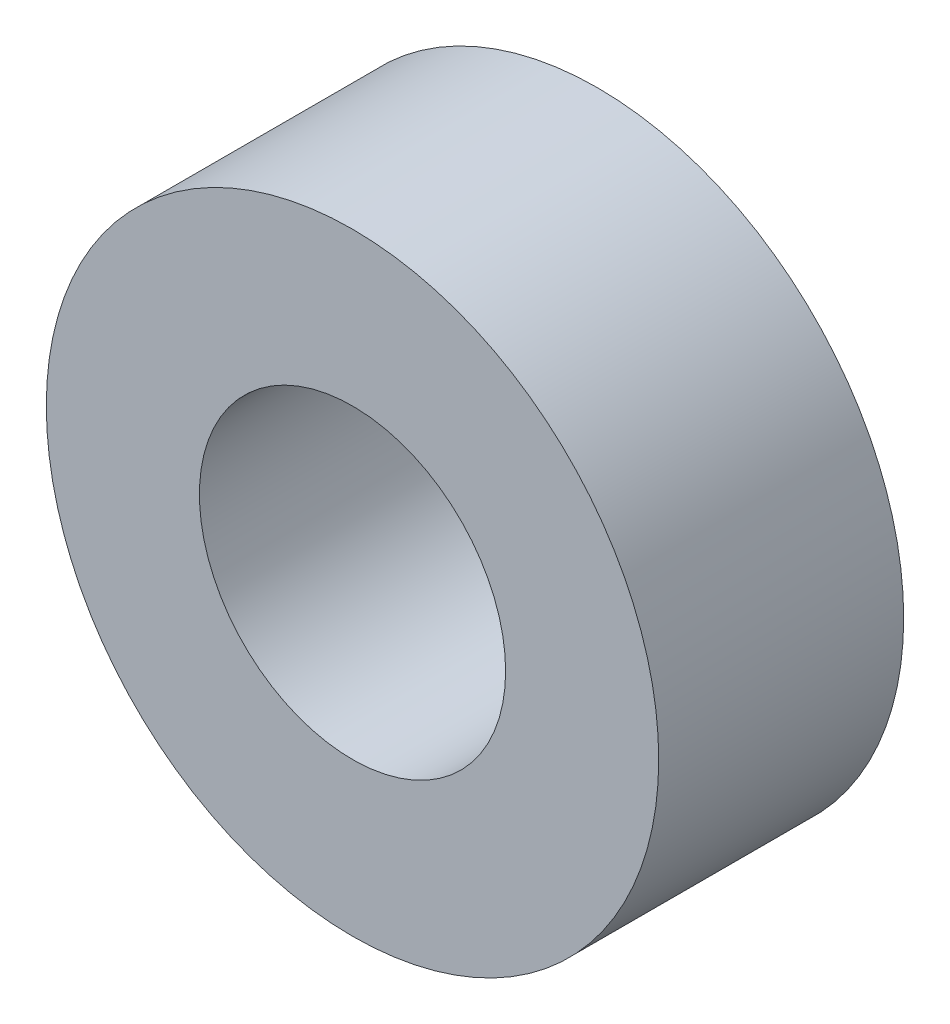
SolidWorks part; units mm, degrees
ref_plane "前视基准面" through (0, 0, 0) normal (0, 0, 1) x (1, 0, 0)
ref_plane "上视基准面" through (0, 0, 0) normal (0, 1, 0) x (1, 0, 0)
ref_plane "右视基准面" through (0, 0, 0) normal (1, 0, 0) x (0, 0, -1)
other "Configuration Table"
sketch "草图1" plane through (0, 0, 0) normal (0, 0, 1) x (1, 0, 0)
  circle A0 centre (0, 0) radius 2.5
  circle A1 centre (0, 0) radius 5
  dimension "D1" = 5
  dimension "D2" = 10
extrude "凸台-拉伸1" add sketch "草图1" along normal blind 4
